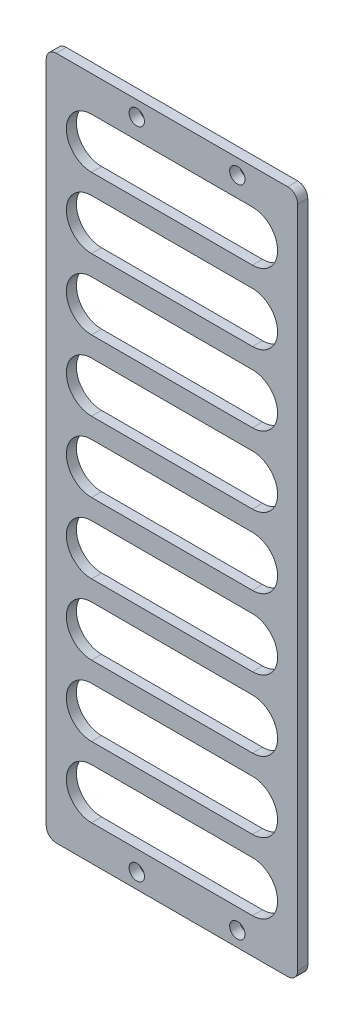
SolidWorks part; units mm, degrees
material "Thornel Mat VMA"
ref_plane "前视基准面" through (0, 0, 0) normal (0, 0, 1) x (1, 0, 0)
ref_plane "上视基准面" through (0, 0, 0) normal (0, 1, 0) x (1, 0, 0)
ref_plane "右视基准面" through (0, 0, 0) normal (1, 0, 0) x (0, 0, -1)
other "Configuration Table"
sketch "草图1" plane through (0, 0, 0) normal (0, 0, 1) x (1, 0, 0)
  line L1 (-25, -68) -> (25, -68)
  line L2 (-25, -68) -> (-25, 68)
  line L3 (-25, 68) -> (25, 68)
  line L4 (25, -68) -> (25, 68)
  line L5 (-25, -68) -> (25, 68) construction
  line L6 (-25, 68) -> (25, -68) construction
  point P0 (0, 0)
  dimension "D1" = 136
  dimension "D2" = 50
extrude "凸台-拉伸1" add sketch "草图1" along normal blind 2
sketch "草图3" plane through (0, 0, 0) normal (0, 0, -1) x (-1, 0, 0)
  circle A0 centre (-13, 65) radius 1.25 construction
  circle A1 centre (7, 65) radius 1.25 construction
  circle A2 centre (-13, 65) radius 1.25 construction
  circle A3 centre (7, 65) radius 1.25 construction
  circle A4 centre (-13, 65) radius 1.525
  circle A5 centre (7, 65) radius 1.525
  dimension "D1" = 3.05
extrude "切除-拉伸1" cut sketch "草图3" against normal blind 10
mirror "镜向1" about plane through (0, 0, 0) normal (0, 1, 0) of "切除-拉伸1"
sketch "草图4" plane through (0, 0, 0) normal (0, 0, -1) x (-1, 0, 0)
  line L0 (16, 0) -> (-16, 0) construction
  line L1 (16, -5) -> (-16, -5)
  line L2 (16, 5) -> (-16, 5)
  line L4 (-25, -68) -> (-25, 68) construction
  arc A0 (16, -5) -> (16, 5) centre (16, 0) ccw
  arc A1 (-16, 5) -> (-16, -5) centre (-16, 0) ccw
  point P2 (0, 0)
  dimension "D2" = 4
  dimension "D1" = 10
extrude "切除-拉伸2" cut sketch "草图4" against normal blind 22
pattern_linear "阵列(线性)1" count 5 spacing 14 along (0, -1, 0) of "切除-拉伸2"
mirror "镜向2" about plane through (0, 0, 0) normal (0, 1, 0) of "阵列(线性)1"
fillet "圆角1" radius 2 4 edges at (25, -68, 1) (-25, -68, 1) (25, 68, 1) (-25, 68, 1)
